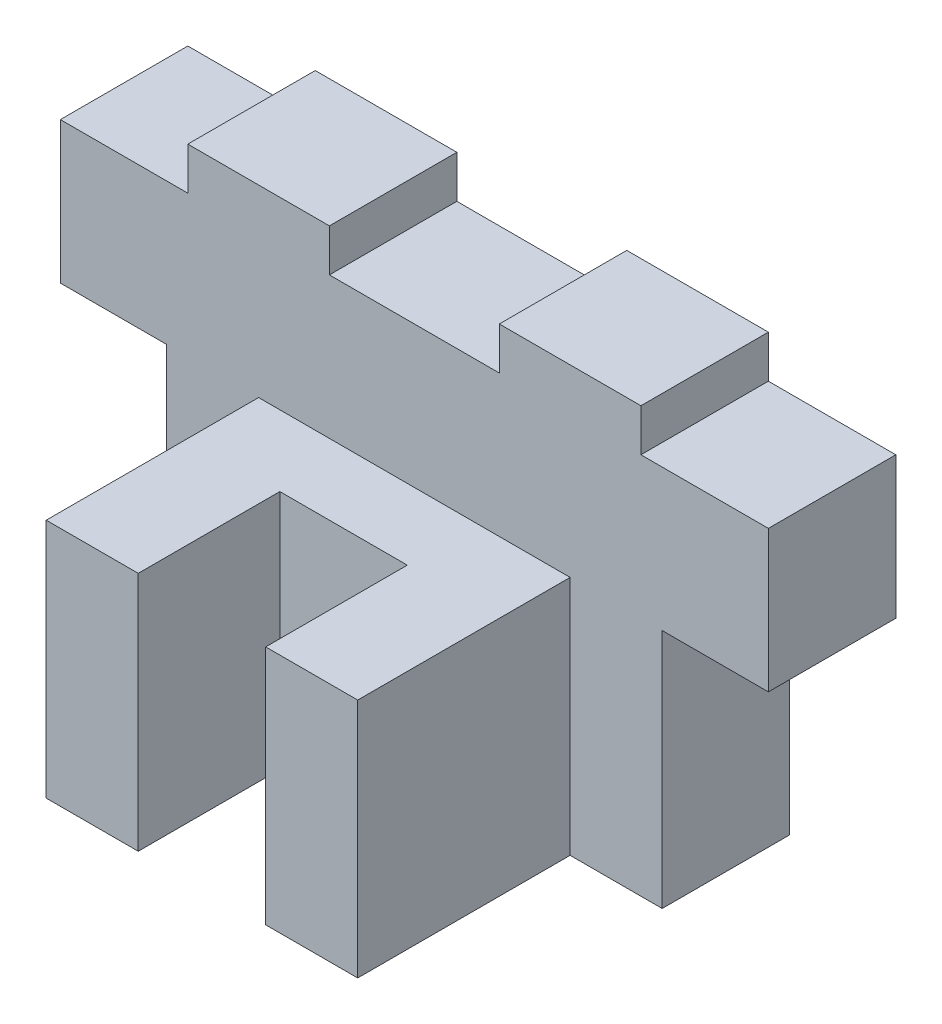
SolidWorks part; units mm, degrees
ref_plane "Спереди" through (0, 0, 0) normal (0, 0, 1) x (1, 0, 0)
ref_plane "Сверху" through (0, 0, 0) normal (0, 1, 0) x (1, 0, 0)
ref_plane "Справа" through (0, 0, 0) normal (1, 0, 0) x (0, 0, -1)
sketch "Эскиз1" plane through (0, 0, 0) normal (0, 0, 1) x (1, 0, 0)
  line L1 (-12.5, -15) -> (12.5, -15)
  line L2 (-12.5, -15) -> (-12.5, 15)
  line L3 (-12.5, 15) -> (12.5, 15)
  line L4 (12.5, -15) -> (12.5, 15)
  line L5 (-12.5, -15) -> (12.5, 15) construction
  line L6 (-12.5, 15) -> (12.5, -15) construction
  line L7 (-12.5, 15) -> (-6.5, 15)
  line L8 (-12.5, 15) -> (-12.5, 12)
  line L9 (-12.5, 12) -> (-6.5, 12)
  line L10 (-6.5, 15) -> (-6.5, 12)
  line L11 (12.5, 15) -> (3.5, 15)
  line L12 (12.5, 15) -> (12.5, 12)
  line L13 (12.5, 12) -> (3.5, 12)
  line L14 (3.5, 15) -> (3.5, 12)
  line L15 (12.5, -15) -> (5, -15)
  line L16 (12.5, -15) -> (12.5, 2)
  line L17 (12.5, 2) -> (5, 2)
  line L18 (5, -15) -> (5, 2)
  point P0 (0, 0)
  dimension "D1" = 25
  dimension "D2" = 30
  dimension "D3" = 3
  dimension "D4" = 6
  dimension "D5" = 9
  dimension "D6" = 10
  dimension "D7" = 7.5
extrude "Бобышка-Вытянуть1" add sketch "Эскиз1" along normal blind 9 contours L1 L18 L17 L4 L13 L14 L3 L10 L9 L2
sketch "Эскиз2" plane through (0, -15, 0) normal (0, -1, 0) x (1, 0, 0)
  line L0 (-12.5, 9) -> (5, 9) construction
  line L1 (-8, 9) -> (-1.5, 9)
  line L2 (-8, 9) -> (-8, 24)
  line L3 (-8, 24) -> (-1.5, 24)
  line L4 (-1.5, 9) -> (-1.5, 24)
  line L6 (-12.5, 9) -> (-8, 9)
  line L7 (-12.5, 9) -> (-12.5, 15.5)
  line L8 (-12.5, 15.5) -> (-8, 15.5)
  line L9 (-8, 9) -> (-8, 15.5)
  line M3 (5, 9) -> (-12.5, 9)
  dimension "D1" = 6.5
  dimension "D2" = 15
  dimension "D3" = 11
extrude "Бобышка-Вытянуть2" add sketch "Эскиз2" against normal up to surface (17 mm away) contours L4 L3 L2 M3 | L8 L7 L2 M3 up to face at (8.75, 2, 4.5)
mirror "Зеркальное отражение1" about plane through (-12.5, 0, 9) normal (-1, 0, 0) of "Бобышка-Вытянуть2", "Бобышка-Вытянуть1"
sketch "Эскиз3" plane through (0, 2, 0) normal (0, 1, 0) x (1, 0, 0)
  line L0 (-8, -24) -> (-8, -15.5) construction
  line L1 (-17, -15.5) -> (-8, -15.5)
  line L2 (-17, -15.5) -> (-17, -14)
  line L3 (-17, -14) -> (-8, -14)
  line L4 (-8, -15.5) -> (-8, -14)
  dimension "D1" = 1.5
extrude "Вырез-Вытянуть1" cut sketch "Эскиз3" against normal through all
